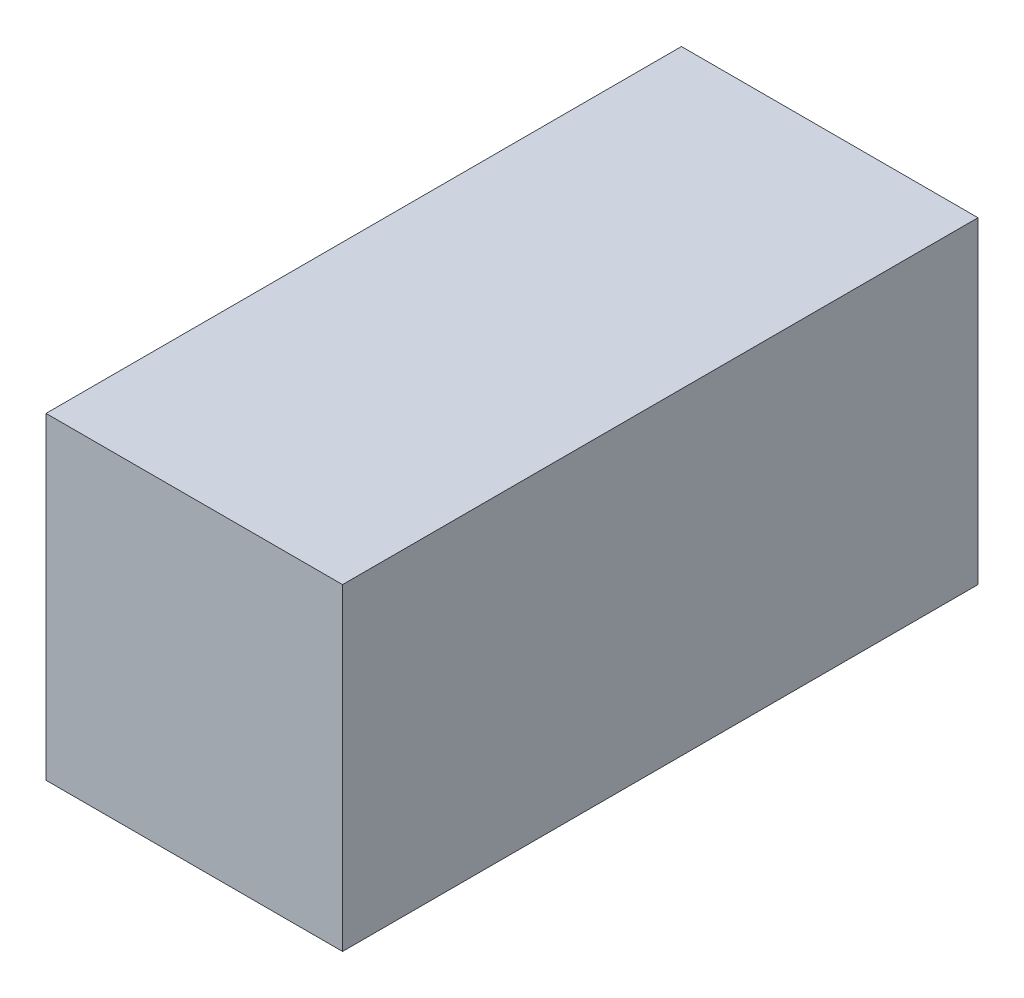
SolidWorks part; units mm, degrees
ref_plane "Front Plane" through (0, 0, 0) normal (0, 0, 1) x (1, 0, 0)
ref_plane "Top Plane" through (0, 0, 0) normal (0, 1, 0) x (1, 0, 0)
ref_plane "Right Plane" through (0, 0, 0) normal (1, 0, 0) x (0, 0, -1)
other "Configuration Table"
sketch "Sketch1" plane through (0, 0, 0) normal (0, 0, 1) x (1, 0, 0)
  line L1 (530, 405) -> (670, 405)
  line L2 (530, 405) -> (530, 555)
  line L3 (530, 555) -> (670, 555)
  line L4 (670, 405) -> (670, 555)
extrude "STORE_klape_kaset_kati_donmus_kap_4_1" add sketch "Sketch1" against normal blind 300 from offset 100 separate body
